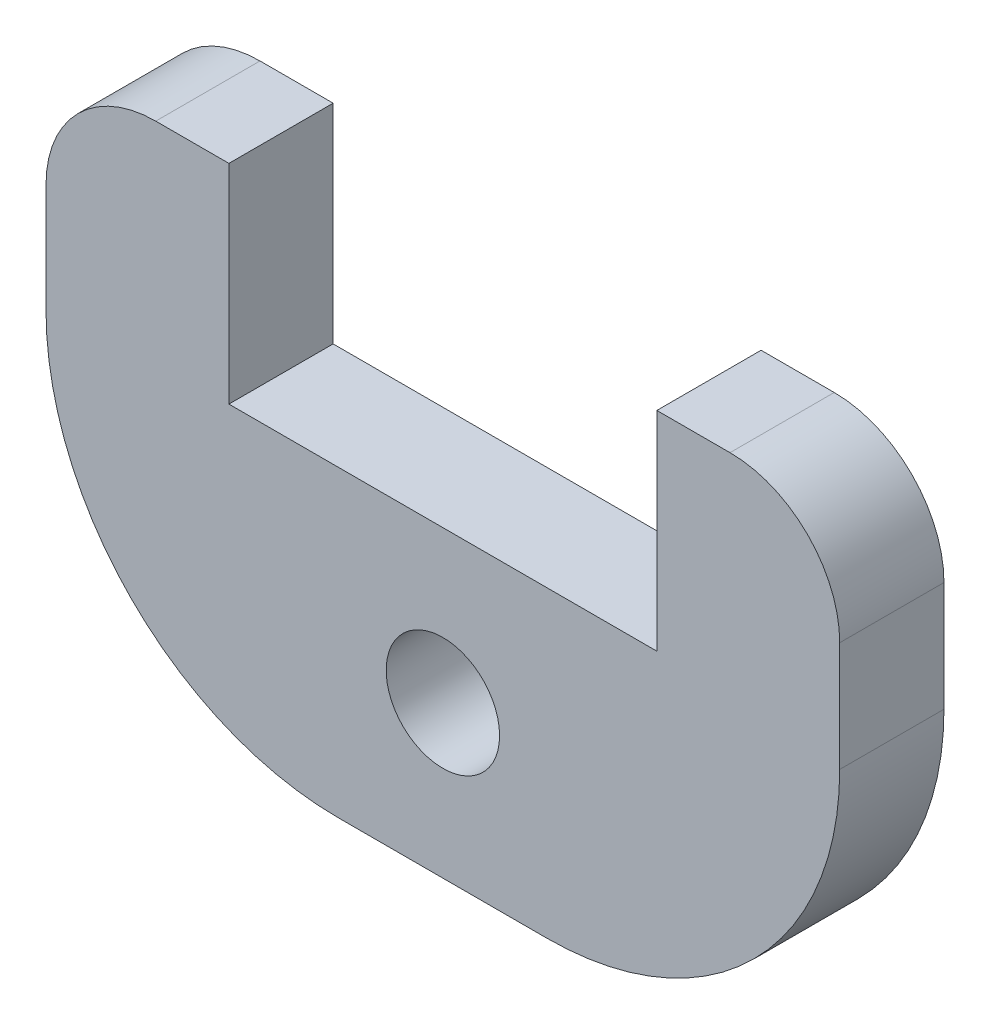
SolidWorks part; units mm, degrees
ref_plane "Front" through (0, 0, 0) normal (0, 0, 1) x (1, 0, 0)
ref_plane "Top" through (0, 0, 0) normal (0, 1, 0) x (1, 0, 0)
ref_plane "Right" through (0, 0, 0) normal (1, 0, 0) x (0, 0, -1)
sketch "Sketch1" plane through (0, 0, 0) normal (0, 0, 1) x (1, 0, 0)
  line L0 (5.85, 7) -> (10.85, 7)
  line L1 (-10.85, 7) -> (-5.85, 7)
  line L2 (-10.85, 7) -> (-10.85, -7)
  line L3 (-10.85, -7) -> (10.85, -7)
  line L4 (10.85, 7) -> (10.85, -7)
  line L5 (-10.85, 7) -> (10.85, -7) construction
  line L6 (-10.85, -7) -> (10.85, 7) construction
  line L8 (-5.85, 7) -> (-5.85, 1.3)
  line L9 (-5.85, 1.3) -> (5.85, 1.3)
  line L10 (5.85, 7) -> (5.85, 1.3)
  point P0 (0, 0)
  dimension "D1" = 11.7
  dimension "D2" = 5.7
  dimension "D3" = 14
  dimension "D4" = 5
extrude "Boss-Extrude1" add sketch "Sketch1" along normal blind 2.85
sketch "Sketch2" plane through (0, 0, 2.85) normal (0, 0, 1) x (1, 0, 0)
  line L0 (0, -7) -> (0, -2.85) construction
  line L1 (-10.85, -7) -> (10.85, -7) construction
  line L2 (0, -2.85) -> (0, 1.3) construction
  line L3 (5.85, 1.3) -> (-5.85, 1.3) construction
  circle A0 centre (0, -2.85) radius 1.55
  dimension "D1" = 3.1
extrude "Cut-Extrude1" cut sketch "Sketch2" against normal through all
fillet "Fillet1" radius 8 2 edges at (-10.85, -7, 1.425) (10.85, -7, 1.425)
fillet "Fillet2" radius 3 2 edges at (10.85, 7, 1.425) (-10.85, 7, 1.425)
